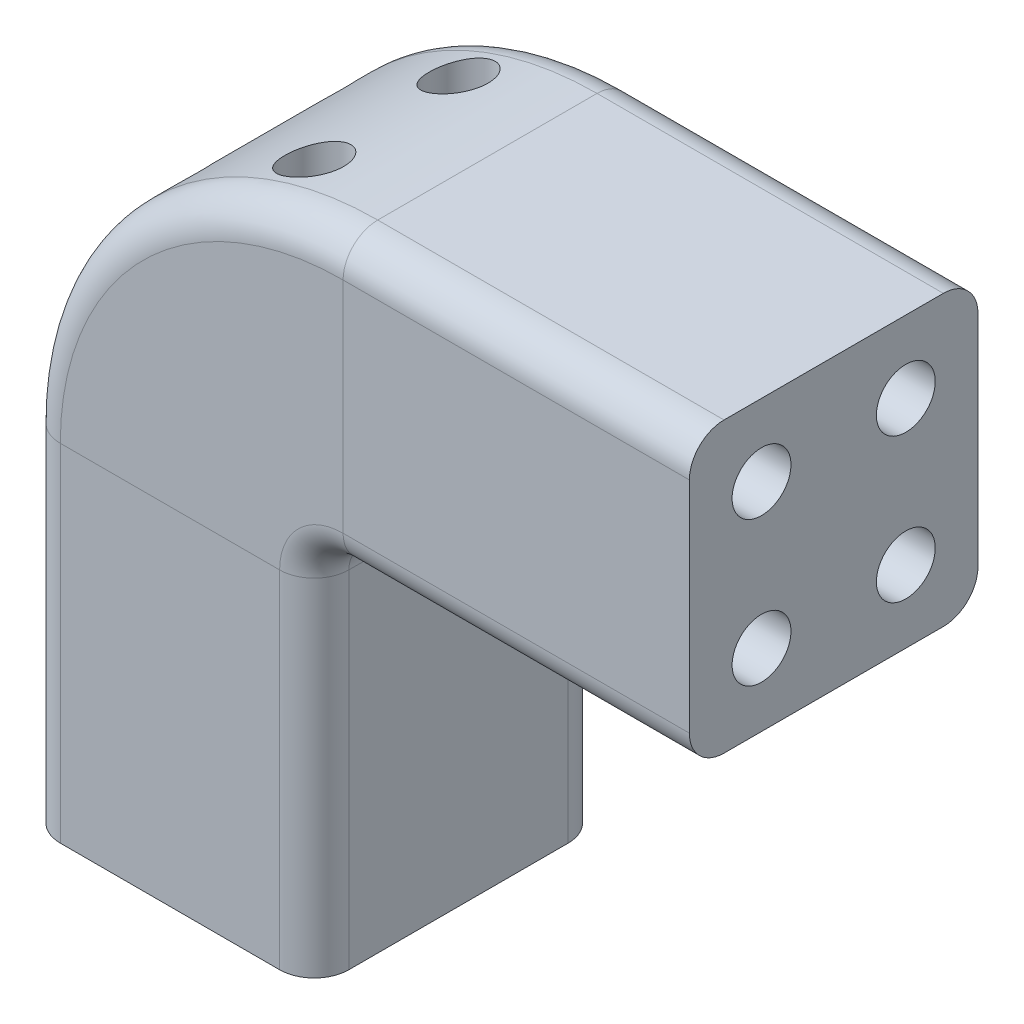
SolidWorks part; units mm, degrees
ref_plane "前视基准面" through (0, 0, 0) normal (0, 0, 1) x (1, 0, 0)
ref_plane "上视基准面" through (0, 0, 0) normal (0, 1, 0) x (1, 0, 0)
ref_plane "右视基准面" through (0, 0, 0) normal (1, 0, 0) x (0, 0, -1)
sketch "草图1" plane through (0, 0, 0) normal (0, 1, 0) x (1, 0, 0)
  line L1 (-9.5, 12.5) -> (9.5, 12.5)
  line L2 (-12.5, 9.5) -> (-12.5, -9.5)
  line L3 (-9.5, -12.5) -> (9.5, -12.5)
  line L4 (12.5, 9.5) -> (12.5, -9.5)
  line L5 (-12.5, 12.5) -> (12.5, -12.5) construction
  line L6 (-12.5, -12.5) -> (12.5, 12.5) construction
  arc A0 (-12.5, -9.5) -> (-9.5, -12.5) centre (-9.5, -9.5) ccw
  arc A1 (9.5, -12.5) -> (12.5, -9.5) centre (9.5, -9.5) ccw
  arc A2 (9.5, 12.5) -> (12.5, 9.5) centre (9.5, 9.5) cw
  arc A3 (-9.5, 12.5) -> (-12.5, 9.5) centre (-9.5, 9.5) ccw
  point P0 (0, 0)
  dimension "D1" = 3
  dimension "D2" = 25
sketch "草图2" plane through (0, 0, 0) normal (0, 0, 1) x (1, 0, 0)
  line L0 (0, 0) -> (0, 30)
  line L1 (-9.5, 0) -> (9.5, 0) construction
  line L2 (15, 45) -> (45, 45)
  line L3 (15, 30) -> (0, 30) construction
  arc A0 (0, 30) -> (15, 45) centre (15, 30) cw
  dimension "D1" = 15
  dimension "D2" = 30
  dimension "D3" = 30
sweep "扫描1" add profiles "草图1" path "草图2"
sketch "草图3" plane through (45, 0, 0) normal (1, 0, 0) x (0, 0, -1)
  line L1 (12.5, 35.5) -> (12.5, 54.5) construction
  line L3 (-12.5, 57.5) -> (12.5, 57.5) construction
  line L5 (-12.5, 57.5) -> (-12.5, 32.5) construction
  line L6 (-12.5, 32.5) -> (12.5, 32.5) construction
  line L11 (12.5, 57.5) -> (12.5, 32.5) construction
  line L12 (-12.5, 57.5) -> (12.5, 32.5) construction
  line L13 (-12.5, 32.5) -> (12.5, 57.5) construction
  line L14 (9.5, 57.5) -> (-9.5, 57.5) construction
  line L15 (-12.5, 54.5) -> (-12.5, 35.5) construction
  line L16 (-9.5, 32.5) -> (9.5, 32.5) construction
  circle A6 centre (0, 45) radius 8.8388 construction
  circle A7 centre (6.25, 51.25) radius 2.55
  circle A8 centre (6.25, 38.75) radius 2.55
  circle A9 centre (-6.25, 38.75) radius 2.55
  circle A10 centre (-6.25, 51.25) radius 2.55
  point P0 (0, 45)
  dimension "D1" = 12.5
  dimension "D2" = 5.1
extrude "切除-拉伸1" cut sketch "草图3" against normal blind 30
sketch "草图5" plane through (0, 0, 0) normal (0, -1, 0) x (1, 0, 0)
  line L0 (-12.6788, 12.6788) -> (12.6788, -12.6788) construction
  line L1 (-11.6342, -11.6342) -> (11.6342, 11.6342) construction
  line L2 (0, 0) -> (0, 3.5605) construction
  circle A0 centre (0, 0) radius 8.8388 construction
  circle A1 centre (-6.25, 6.25) radius 2.55
  circle A2 centre (6.25, 6.25) radius 2.55
  circle A3 centre (-6.25, -6.25) radius 2.55
  circle A4 centre (6.25, -6.25) radius 2.55
  point P16 (-5.9831, 5.9831)
  point P17 (-5.9798, 5.9798)
  point P18 (-6.2149, 6.2149)
  point P19 (8.4525, -8.4525)
  point P20 (-6.2724, 6.1219)
  point P21 (-4.6591, 4.6591)
  point P22 (0, 0)
  dimension "D3" = 5.1
  dimension "D1" = 45
  dimension "D2" = 12.5
extrude "切除-拉伸2" cut sketch "草图5" against normal through all
